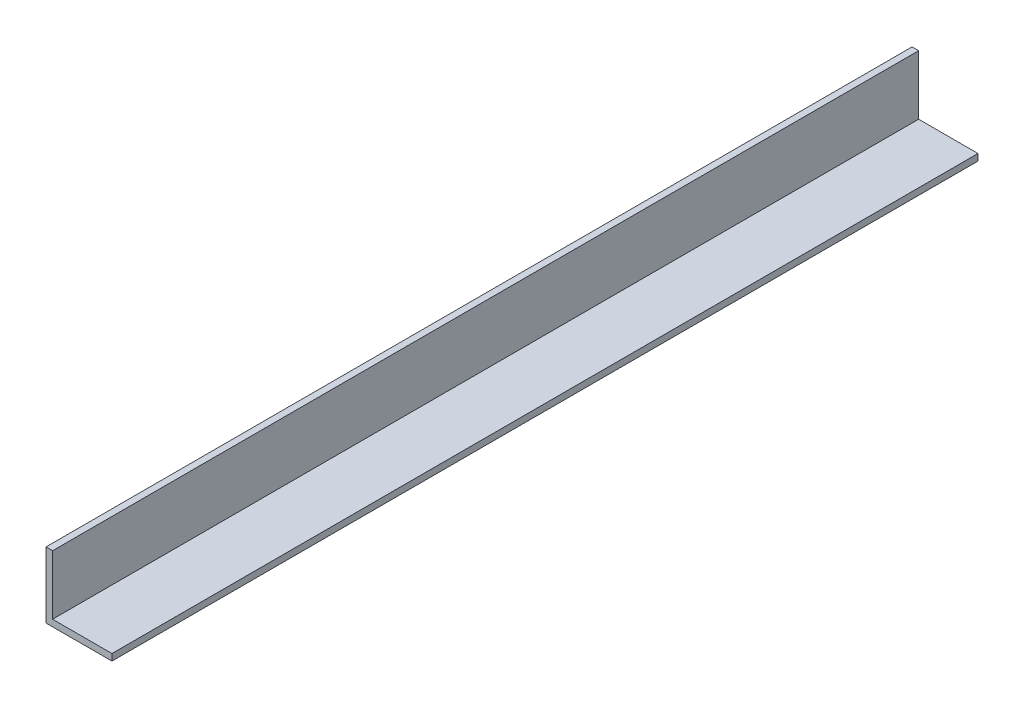
SolidWorks part; units mm, degrees
material "Ferro duttile"
ref_plane "Piano frontale" through (0, 0, 0) normal (0, 0, 1) x (1, 0, 0)
ref_plane "Piano superiore" through (0, 0, 0) normal (0, 1, 0) x (1, 0, 0)
ref_plane "Piano destro" through (0, 0, 0) normal (1, 0, 0) x (0, 0, -1)
sketch "Schizzo1" plane through (0, 0, 0) normal (0, 0, 1) x (1, 0, 0)
  line L0 (0, 30) -> (0, 0)
  line L1 (0, 0) -> (30, 0)
  line L2 (30, 0) -> (30, 3)
  line L3 (30, 3) -> (3, 3)
  line L4 (3, 3) -> (3, 30)
  line L5 (3, 30) -> (0, 30)
  dimension "D1" = 3
  dimension "D2" = 3
  dimension "D3" = 30
  dimension "D4" = 30
extrude "Estrusione-Estrusione1" add sketch "Schizzo1" along normal blind 394
